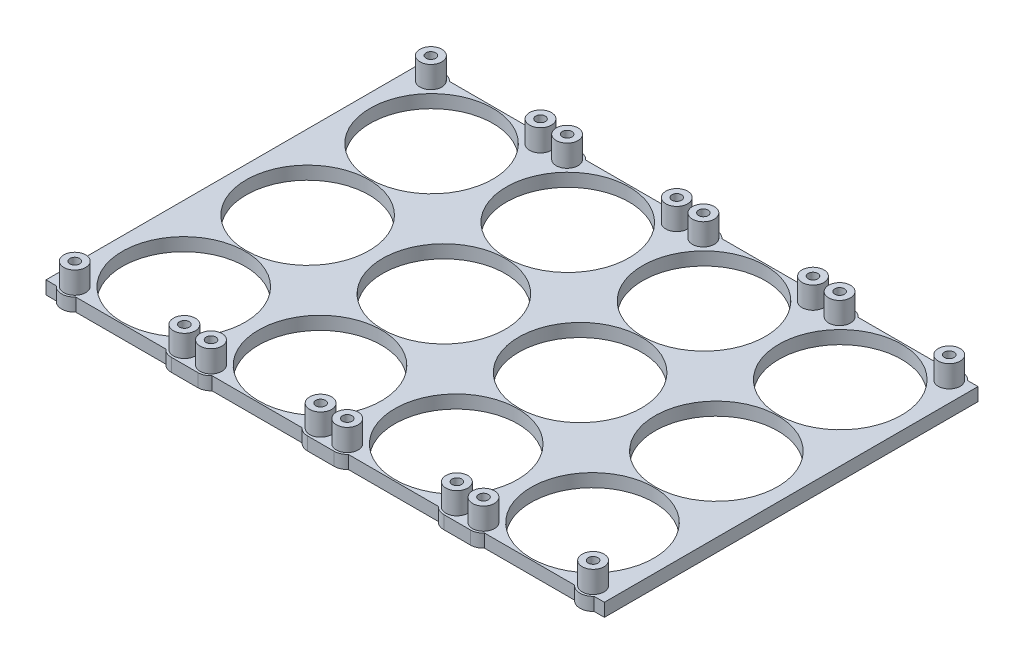
SolidWorks part; units mm, degrees
ref_plane "Front Plane" through (0, 0, 0) normal (0, 0, 1) x (1, 0, 0)
ref_plane "Top Plane" through (0, 0, 0) normal (0, 1, 0) x (1, 0, 0)
ref_plane "Right Plane" through (0, 0, 0) normal (1, 0, 0) x (0, 0, -1)
sketch "Sketch1" plane through (0, 0, 0) normal (0, 1, 0) x (1, 0, 0)
  line L0 (11.122, -9.411) -> (11.122, -19.379)
  line L1 (0, 0) -> (127.76, 0)
  line L2 (0, 0) -> (0, -85.48)
  line L3 (0, -85.48) -> (127.76, -85.48)
  line L4 (127.76, 0) -> (127.76, -85.48)
  line L5 (23.122, -9.411) -> (23.122, -19.379)
  line L6 (42.294, -9.411) -> (42.294, -19.379)
  line L7 (54.294, -9.411) -> (54.294, -19.379)
  line L8 (73.466, -9.411) -> (73.466, -19.379)
  line L9 (85.466, -9.411) -> (85.466, -19.379)
  line L10 (104.638, -9.411) -> (104.638, -19.379)
  line L11 (116.638, -9.411) -> (116.638, -19.379)
  line L12 (42.294, -37.756) -> (42.294, -47.724)
  line L13 (54.294, -37.756) -> (54.294, -47.724)
  line L14 (73.466, -37.756) -> (73.466, -47.724)
  line L15 (85.466, -37.756) -> (85.466, -47.724)
  line L16 (104.638, -37.756) -> (104.638, -47.724)
  line L17 (116.638, -37.756) -> (116.638, -47.724)
  line L18 (42.294, -66.101) -> (42.294, -76.069)
  line L19 (54.294, -66.101) -> (54.294, -76.069)
  line L20 (73.466, -66.101) -> (73.466, -76.069)
  line L21 (85.466, -66.101) -> (85.466, -76.069)
  line L22 (104.638, -66.101) -> (104.638, -76.069)
  line L23 (116.638, -66.101) -> (116.638, -76.069)
  line L24 (11.122, -37.756) -> (11.122, -47.724)
  line L25 (23.122, -37.756) -> (23.122, -47.724)
  line L26 (11.122, -66.101) -> (11.122, -76.069)
  line L27 (23.122, -66.101) -> (23.122, -76.069)
  circle A2 centre (17.122, -14.395) radius 14.05
  circle A12 centre (48.294, -14.395) radius 14.05
  circle A13 centre (79.466, -14.395) radius 14.05
  circle A14 centre (110.638, -14.395) radius 14.05
  circle A15 centre (48.294, -42.74) radius 14.05
  circle A16 centre (79.466, -42.74) radius 14.05
  circle A17 centre (110.638, -42.74) radius 14.05
  circle A18 centre (48.294, -71.085) radius 14.05
  circle A19 centre (79.466, -71.085) radius 14.05
  circle A20 centre (110.638, -71.085) radius 14.05
  circle A21 centre (17.122, -42.74) radius 14.05
  circle A22 centre (17.122, -71.085) radius 14.05
  arc A23 (11.122, -19.379) -> (23.122, -19.379) centre (17.122, -14.395) ccw
  arc A24 (23.122, -9.411) -> (11.122, -9.411) centre (17.122, -14.395) ccw
  arc A25 (42.294, -19.379) -> (54.294, -19.379) centre (48.294, -14.395) ccw
  arc A26 (54.294, -9.411) -> (42.294, -9.411) centre (48.294, -14.395) ccw
  arc A27 (73.466, -19.379) -> (85.466, -19.379) centre (79.466, -14.395) ccw
  arc A28 (85.466, -9.411) -> (73.466, -9.411) centre (79.466, -14.395) ccw
  arc A29 (104.638, -19.379) -> (116.638, -19.379) centre (110.638, -14.395) ccw
  arc A30 (116.638, -9.411) -> (104.638, -9.411) centre (110.638, -14.395) ccw
  arc A31 (42.294, -47.724) -> (54.294, -47.724) centre (48.294, -42.74) ccw
  arc A32 (54.294, -37.756) -> (42.294, -37.756) centre (48.294, -42.74) ccw
  arc A33 (73.466, -47.724) -> (85.466, -47.724) centre (79.466, -42.74) ccw
  arc A34 (85.466, -37.756) -> (73.466, -37.756) centre (79.466, -42.74) ccw
  arc A35 (104.638, -47.724) -> (116.638, -47.724) centre (110.638, -42.74) ccw
  arc A36 (116.638, -37.756) -> (104.638, -37.756) centre (110.638, -42.74) ccw
  arc A37 (42.294, -76.069) -> (54.294, -76.069) centre (48.294, -71.085) ccw
  arc A38 (54.294, -66.101) -> (42.294, -66.101) centre (48.294, -71.085) ccw
  arc A39 (73.466, -76.069) -> (85.466, -76.069) centre (79.466, -71.085) ccw
  arc A40 (85.466, -66.101) -> (73.466, -66.101) centre (79.466, -71.085) ccw
  arc A41 (104.638, -76.069) -> (116.638, -76.069) centre (110.638, -71.085) ccw
  arc A42 (116.638, -66.101) -> (104.638, -66.101) centre (110.638, -71.085) ccw
  arc A43 (11.122, -47.724) -> (23.122, -47.724) centre (17.122, -42.74) ccw
  arc A44 (23.122, -37.756) -> (11.122, -37.756) centre (17.122, -42.74) ccw
  arc A45 (11.122, -76.069) -> (23.122, -76.069) centre (17.122, -71.085) ccw
  arc A46 (23.122, -66.101) -> (11.122, -66.101) centre (17.122, -71.085) ccw
  dimension "D3" = 4
  dimension "D4" = 14.395
  dimension "D9" = 15.6
  dimension "D11" = 28.1
  dimension "D1" = 127.76
  dimension "D2" = 85.48
  dimension "D5" = 3
  dimension "D6" = 14.395
  dimension "D7" = 17.122
  dimension "D8" = 17.122
  dimension "D10" = 12
  dimension "D12" = 4
  dimension "D13" = 3
extrude "Boss-Extrude3" add sketch "Sketch1" along normal blind 3 contours L4 L1 L2 L3 A22 A21 A20 A19 A18 A17 A16 A15 A14 A13 A12 A2
sketch "Sketch2" plane through (0, 0, 0) normal (0, -1, 0) x (1, 0, 0)
  line L0 (0, 0) -> (127.76, 0) construction
  line L1 (0, 85.48) -> (127.76, 85.48) construction
  line L2 (4.582, 2) -> (29.662, 2) construction
  line L3 (4.582, 83.48) -> (29.662, 83.48) construction
  line L4 (17.122, 83.48) -> (17.122, 2) construction
  line L5 (35.754, 2) -> (60.834, 2) construction
  line L6 (35.754, 83.48) -> (60.834, 83.48) construction
  line L7 (48.294, 83.48) -> (48.294, 2) construction
  line L8 (66.926, 2) -> (92.006, 2) construction
  line L9 (66.926, 83.48) -> (92.006, 83.48) construction
  line L10 (79.466, 83.48) -> (79.466, 2) construction
  line L11 (98.098, 2) -> (123.178, 2) construction
  line L12 (98.098, 83.48) -> (123.178, 83.48) construction
  line L13 (110.638, 83.48) -> (110.638, 2) construction
  line L14 (3.072, 42.74) -> (31.172, 42.74) construction
  line L15 (96.588, 42.74) -> (124.688, 42.74) construction
  line L17 (29.662, 5) -> (35.754, 5)
  line L18 (29.662, 5) -> (29.662, -1)
  line L19 (29.662, -1) -> (35.754, -1)
  line L20 (35.754, 5) -> (35.754, -1)
  line L21 (60.834, 5) -> (66.926, 5)
  line L22 (60.834, 5) -> (60.834, -1)
  line L23 (60.834, -1) -> (66.926, -1)
  line L24 (66.926, 5) -> (66.926, -1)
  line L25 (92.006, 5) -> (98.098, 5)
  line L26 (92.006, 5) -> (92.006, -1)
  line L27 (92.006, -1) -> (98.098, -1)
  line L28 (98.098, 5) -> (98.098, -1)
  line L29 (92.006, 86.48) -> (98.098, 86.48)
  line L30 (92.006, 86.48) -> (92.006, 80.48)
  line L31 (92.006, 80.48) -> (98.098, 80.48)
  line L32 (98.098, 86.48) -> (98.098, 80.48)
  line L33 (66.926, 86.48) -> (60.834, 86.48)
  line L34 (66.926, 86.48) -> (66.926, 80.48)
  line L35 (66.926, 80.48) -> (60.834, 80.48)
  line L36 (60.834, 86.48) -> (60.834, 80.48)
  line L37 (29.662, 86.48) -> (35.754, 86.48)
  line L38 (29.662, 86.48) -> (29.662, 80.48)
  line L39 (29.662, 80.48) -> (35.754, 80.48)
  line L40 (35.754, 86.48) -> (35.754, 80.48)
  circle A0 centre (4.582, 2) radius 3
  circle A1 centre (29.662, 2) radius 3
  circle A2 centre (29.662, 83.48) radius 3
  circle A3 centre (4.582, 83.48) radius 3
  circle A4 centre (35.754, 2) radius 3
  circle A5 centre (60.834, 2) radius 3
  circle A6 centre (60.834, 83.48) radius 3
  circle A7 centre (35.754, 83.48) radius 3
  circle A8 centre (66.926, 2) radius 3
  circle A9 centre (92.006, 2) radius 3
  circle A10 centre (92.006, 83.48) radius 3
  circle A11 centre (66.926, 83.48) radius 3
  circle A12 centre (98.098, 2) radius 3
  circle A13 centre (123.178, 2) radius 3
  circle A14 centre (123.178, 83.48) radius 3
  circle A15 centre (98.098, 83.48) radius 3
  circle A16 centre (17.122, 42.74) radius 14.05 construction
  circle A17 centre (110.638, 42.74) radius 14.05 construction
  point P49 (110.638, 42.74)
  point P56 (17.122, 42.74)
  line M15 (127.76, 85.48) -> (0, 85.48)
  line M17 (0, 0) -> (127.76, 0)
  dimension "D1" = 6
  dimension "D2" = 2
  dimension "D5" = 25.08
  dimension "D6" = 2
  dimension "D3" = 2
  dimension "D4" = 2
  dimension "D7" = 4
extrude "Boss-Extrude4" add sketch "Sketch2" against normal up to surface (3 mm away) contours A0 M17 | A1 L18 M17 | L18 A1 M17 | A4 A1 L19 M17 | A4 L20 M17 | L20 A4 M17 | A5 L22 M17 | L22 A5 M17 | A8 A5 L23 M17 | A8 L24 M17 | L24 A8 M17 | A9 L26 M17 | L26 A9 M17 | A12 A9 L27 M17 | A12 L28 M17 | L28 A12 M17 | A13 M17 | A14 M15 | A15 L32 M15 | L32 A15 M15 | A15 L29 A10 M15 | A10 L30 M15 | L30 A10 M15 | A11 L34 M15 | L34 A11 M15 | A11 L33 A6 M15 | A6 L36 M15 | L36 A6 M15 | A3 M15 | L38 A2 M15 | A2 L38 M15 | A7 L37 A2 M15 | L40 A7 M15 | A7 L40 M15 up to face at (17.122, 3, 85.135)
sketch "Sketch7" plane through (0, 0, 0) normal (0, 1, 0) x (1, 0, 0)
  circle A0 centre (4.582, -83.48) radius 2.5
  circle A1 centre (29.662, -83.48) radius 2.5
  circle A2 centre (29.662, -2) radius 2.5
  circle A3 centre (4.582, -2) radius 2.5
  circle A4 centre (35.754, -83.48) radius 2.5
  circle A5 centre (60.834, -83.48) radius 2.5
  circle A6 centre (60.834, -2) radius 2.5
  circle A7 centre (35.754, -2) radius 2.5
  circle A8 centre (66.926, -83.48) radius 2.5
  circle A9 centre (92.006, -83.48) radius 2.5
  circle A10 centre (92.006, -2) radius 2.5
  circle A11 centre (66.926, -2) radius 2.5
  circle A12 centre (98.098, -83.48) radius 2.5
  circle A13 centre (123.178, -83.48) radius 2.5
  circle A14 centre (123.178, -2) radius 2.5
  circle A15 centre (98.098, -2) radius 2.5
  dimension "D1" = 5
  dimension "D2" = 2
  dimension "D3" = 2
  dimension "D4" = 4
extrude "Boss-Extrude5" add sketch "Sketch7" along normal blind 5 from surface at 3 starting at face at (17.122, 3, 85.135)
sketch "Sketch4" plane through (0, 3, 0) normal (0, 1, 0) x (1, 0, 0)
  circle A0 centre (4.582, -83.48) radius 1.1
  circle A1 centre (29.662, -83.48) radius 1.1
  circle A2 centre (29.662, -2) radius 1.1
  circle A3 centre (4.582, -2) radius 1.1
  circle A4 centre (35.754, -83.48) radius 1.1
  circle A5 centre (60.834, -83.48) radius 1.1
  circle A6 centre (60.834, -2) radius 1.1
  circle A7 centre (35.754, -2) radius 1.1
  circle A8 centre (66.926, -83.48) radius 1.1
  circle A9 centre (92.006, -83.48) radius 1.1
  circle A10 centre (92.006, -2) radius 1.1
  circle A11 centre (66.926, -2) radius 1.1
  circle A12 centre (98.098, -83.48) radius 1.1
  circle A13 centre (123.178, -83.48) radius 1.1
  circle A14 centre (123.178, -2) radius 1.1
  circle A15 centre (98.098, -2) radius 1.1
  dimension "D1" = 2.2
  dimension "D2" = 2
  dimension "D3" = 2
extrude "Cut-Extrude1" cut sketch "Sketch4" against normal blind 5 from surface at 5 starting at face at (4.582, 8, 85.98)
